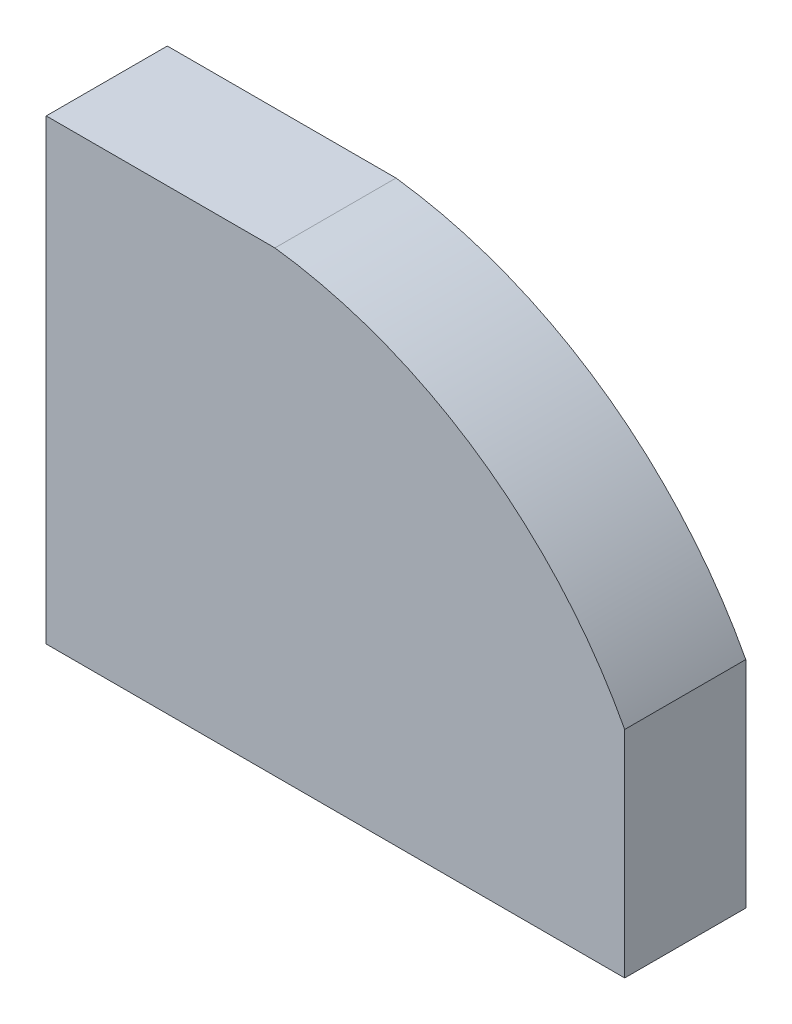
SolidWorks part; units mm, degrees
ref_plane "前视基准面" through (0, 0, 0) normal (0, 0, 1) x (1, 0, 0)
ref_plane "上视基准面" through (0, 0, 0) normal (0, 1, 0) x (1, 0, 0)
ref_plane "右视基准面" through (0, 0, 0) normal (1, 0, 0) x (0, 0, -1)
sketch "草图1" plane through (0, 0, 0) normal (0, 0, 1) x (1, 0, 0)
  line L0 (43, 0) -> (43, 16)
  line L1 (0, 34) -> (43, 34)
  line L2 (0, 34) -> (0, 0)
  line L3 (0, 0) -> (43, 0)
  line L4 (43, 34) -> (43, 0)
  line L5 (0, 34) -> (17, 34)
  arc A0 (17, 34) -> (43, 16) centre (12.6923, 0) cw
  point P8 (0, 0)
  point P9 (0, 0)
  point P10 (12.6923, 0)
  point P11 (12.6923, 0)
  point P12 (0, 0)
  point P13 (0, 0)
  point P14 (12.6923, 0)
  point P15 (0, 0)
  dimension "D1" = 34
  dimension "D2" = 43
  dimension "D3" = 16
  dimension "D4" = 17
extrude "凸台-拉伸1" add sketch "草图1" along normal blind 9 contours A0 L1 L2 L3 L0
sketch "草图2" plane through (0, 0, 0) normal (0, -1, 0) x (1, 0, 0)
  line L2 (21.5, -991) -> (21.5, 49009) construction
  line L3 (0, 9) -> (43, 9) construction
  line L4 (0, 0) -> (43, 0) construction
  line L5 (0, 9) -> (0, 0) construction
  circle A0 centre (3.75, 3.75) radius 1.75
  circle A1 centre (39.25, 3.75) radius 1.75
  point P9 (21.5, 9)
  dimension "D1" = 3.5
  dimension "D2" = 3.75
  dimension "D3" = 3.75
extrude "切除-拉伸1" cut sketch "草图2" against normal blind 5
